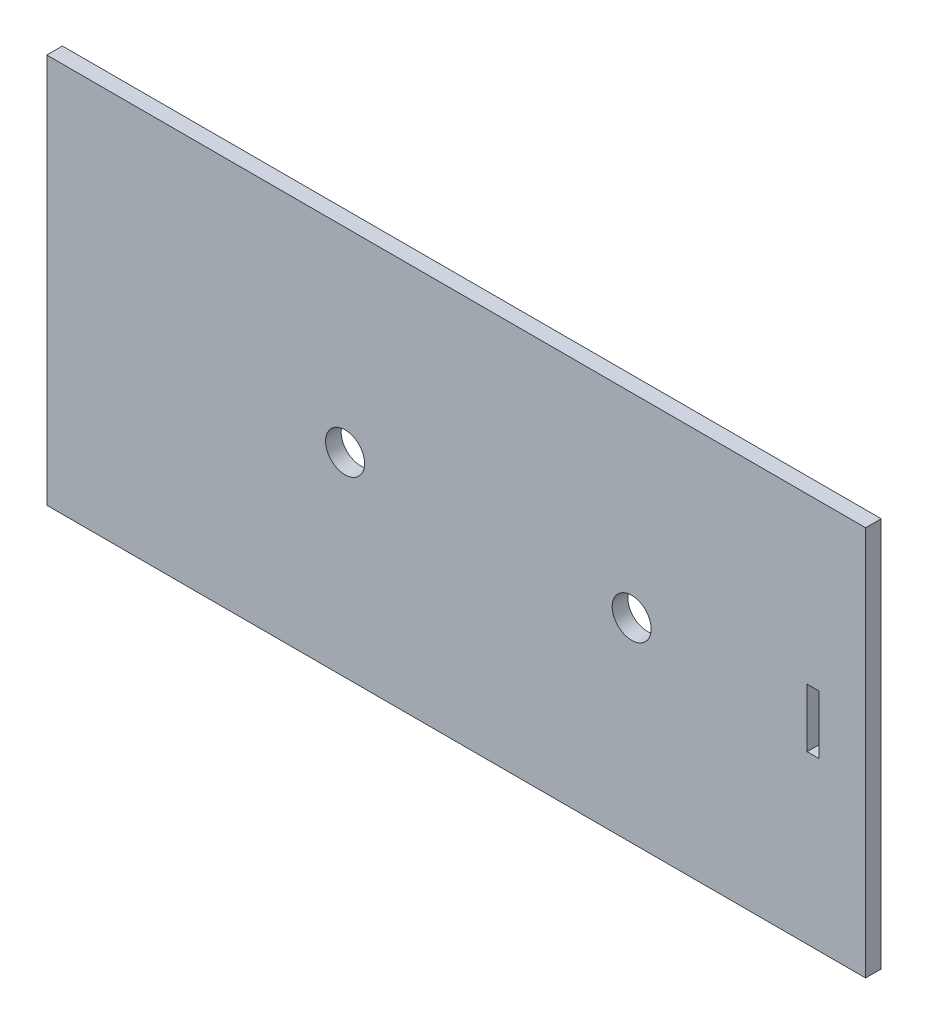
SolidWorks part; units mm, degrees
ref_plane "Front Plane" through (0, 0, 0) normal (0, 0, 1) x (1, 0, 0)
ref_plane "Top Plane" through (0, 0, 0) normal (0, 1, 0) x (1, 0, 0)
ref_plane "Right Plane" through (0, 0, 0) normal (1, 0, 0) x (0, 0, -1)
sketch "Sketch1" plane through (0, 0, 0) normal (0, 0, 1) x (1, 0, 0)
  line L1 (-150, -50) -> (60, -50)
  line L2 (-150, -50) -> (-150, 50)
  line L3 (-150, 50) -> (60, 50)
  line L4 (60, -50) -> (60, 50)
  line L7 (45, 7.7621) -> (48, 7.7621)
  line L8 (45, 7.7621) -> (45, -7.2379)
  line L9 (45, -7.2379) -> (48, -7.2379)
  line L10 (48, 7.7621) -> (48, -7.2379)
  line L11 (45, 7.7621) -> (48, -7.2379) construction
  line L12 (45, -7.2379) -> (48, 7.7621) construction
  circle A0 centre (0, 0) radius 5
  circle A2 centre (-73.5, 0) radius 5
  point P1 (0, 0)
  point P8 (46.5, 0.2621)
  dimension "D3" = 10
  dimension "D4" = 0
  dimension "D5" = 3
  dimension "D1" = 150
  dimension "D2" = 100
  dimension "D6" = 15
  dimension "D7" = 45
  dimension "D8" = 73.5
  dimension "D9" = 60
extrude "Boss-Extrude1" add sketch "Sketch1" along normal blind 4
